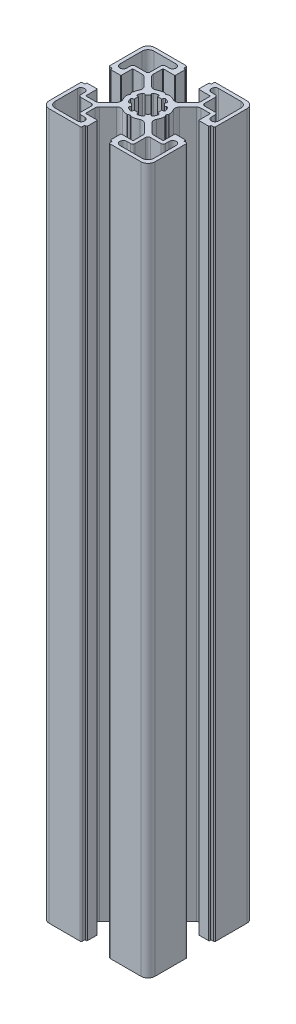
SolidWorks part; units mm, degrees
ref_plane "Front Plane" through (0, 0, 0) normal (0, 0, 1) x (1, 0, 0)
ref_plane "Top Plane" through (0, 0, 0) normal (0, 1, 0) x (1, 0, 0)
ref_plane "Right Plane" through (0, 0, 0) normal (1, 0, 0) x (0, 0, -1)
sketch "Sketch1" plane through (0, 0, 0) normal (0, 1, 0) x (1, 0, 0)
  line L106 (-18, 9.0002) -> (-18, 10.55)
  line L107 (-21, 18.5) -> (-21, 9.0002)
  line L108 (-9, 21) -> (-18.5, 21)
  line L109 (-10.55, 18) -> (-9, 18)
  line L110 (0.9675, 5.4811) -> (0.8674, 4.9242)
  line L111 (2.864, 4.0985) -> (3.1913, 4.5626)
  line L112 (4.5668, 3.2081) -> (4.0897, 2.8765)
  line L113 (4.9205, 0.8878) -> (5.4897, 0.9862)
  line L114 (5.4898, -0.9862) -> (4.9205, -0.8878)
  line L115 (4.0897, -2.8765) -> (4.5668, -3.2082)
  line L116 (3.1914, -4.5627) -> (2.864, -4.0985)
  line L117 (0.8674, -4.9242) -> (0.9675, -5.4811)
  line L118 (-0.9675, -5.4811) -> (-0.8674, -4.9242)
  line L119 (-2.864, -4.0985) -> (-3.1913, -4.5626)
  line L120 (-4.5668, -3.2082) -> (-4.0897, -2.8765)
  line L121 (-4.9205, -0.8878) -> (-5.4897, -0.9862)
  line L122 (-5.4899, 0.9862) -> (-4.9205, 0.8878)
  line L123 (-4.0897, 2.8765) -> (-4.5668, 3.2081)
  line L124 (-3.1914, 4.5627) -> (-2.864, 4.0985)
  line L125 (-0.8674, 4.9242) -> (-0.9675, 5.4811)
  line L126 (-11.55, 12.55) -> (-11.55, 17)
  line L127 (-17, 11.55) -> (-12.55, 11.55)
  line L128 (-21, -9.0002) -> (-21, -18.5)
  line L129 (-18, -10.55) -> (-18, -9.0002)
  line L130 (-12.55, -11.55) -> (-17, -11.55)
  line L131 (-11.55, -17) -> (-11.55, -12.55)
  line L132 (-9, -18) -> (-10.55, -18)
  line L133 (-18.5, -21) -> (-9, -21)
  line L134 (21, 9.0002) -> (21, 18.5)
  line L135 (18, 10.55) -> (18, 9.0002)
  line L136 (12.55, 11.55) -> (17, 11.55)
  line L137 (11.55, 17) -> (11.55, 12.55)
  line L138 (9, 18) -> (10.55, 18)
  line L139 (18.5, 21) -> (9, 21)
  line L140 (17, -11.55) -> (12.55, -11.55)
  line L141 (18, -9.0002) -> (18, -10.55)
  line L142 (21, -18.5) -> (21, -9.0002)
  line L143 (9, -21) -> (18.5, -21)
  line L144 (10.55, -18) -> (9, -18)
  line L145 (11.55, -12.55) -> (11.55, -17)
  line L146 (7.5635, 5.8587) -> (11.1298, 9.425)
  line L147 (12.5048, 9.9945) -> (16.3169, 9.9945)
  line L148 (16.5169, 9.7945) -> (16.5169, 5.2)
  line L149 (16.7169, 5) -> (20.7196, 5)
  line L150 (21.0196, 5.3) -> (21.0196, 5.5)
  line L151 (21.3196, 5.8) -> (22, 5.8)
  line L152 (22.5, 6.3) -> (22.5, 19.5)
  line L153 (19.5, 22.5) -> (6.3757, 22.5)
  line L154 (5.8757, 22) -> (5.8757, 21.3)
  line L155 (5.5757, 21) -> (5.3, 21)
  line L156 (5, 20.7) -> (5, 16.6668)
  line L157 (5.2, 16.4668) -> (9.9054, 16.4668)
  line L158 (10.1054, 16.2668) -> (10.1054, 12.4716)
  line L159 (9.5196, 11.0574) -> (5.9449, 7.4827)
  line L160 (0.7548, 7.9748) -> (0.1126, 7.6069)
  line L161 (-0.1126, 7.6069) -> (-0.7547, 7.9748)
  line L162 (-5.9449, 7.4827) -> (-9.5196, 11.0574)
  line L163 (-10.1054, 12.4716) -> (-10.1054, 16.2668)
  line L164 (-9.9054, 16.4668) -> (-5.2, 16.4668)
  line L165 (-5, 16.6668) -> (-5, 20.7)
  line L166 (-5.3, 21) -> (-5.5757, 21)
  line L167 (-5.8757, 21.3) -> (-5.8757, 22)
  line L168 (-6.3757, 22.5) -> (-19.5, 22.5)
  line L169 (-22.5, 19.5) -> (-22.5, 6.3)
  line L170 (-22, 5.8) -> (-21.3196, 5.8)
  line L171 (-21.0196, 5.5) -> (-21.0196, 5.3)
  line L172 (-20.7196, 5) -> (-16.7169, 5)
  line L173 (-16.5169, 5.2) -> (-16.5169, 9.7945)
  line L174 (-16.3169, 9.9945) -> (-12.5048, 9.9945)
  line L175 (-11.1298, 9.425) -> (-7.5635, 5.8587)
  line L176 (-7.974, 0.7926) -> (-7.5401, 0.0468)
  line L177 (-7.5401, -0.0468) -> (-7.974, -0.7926)
  line L178 (-7.5635, -5.8587) -> (-11.1298, -9.425)
  line L179 (-12.5048, -9.9945) -> (-16.3169, -9.9945)
  line L180 (-16.5169, -9.7945) -> (-16.5169, -5.2)
  line L181 (-16.7169, -5) -> (-20.7196, -5)
  line L182 (-21.0196, -5.3) -> (-21.0196, -5.5)
  line L183 (-21.3196, -5.8) -> (-22, -5.8)
  line L184 (-22.5, -6.3) -> (-22.5, -19.5)
  line L185 (-19.5, -22.5) -> (-6.3757, -22.5)
  line L186 (-5.8757, -22) -> (-5.8757, -21.3)
  line L187 (-5.5757, -21) -> (-5.3, -21)
  line L188 (-5, -20.7) -> (-5, -16.6668)
  line L189 (-5.2, -16.4668) -> (-9.9054, -16.4668)
  line L190 (-10.1054, -16.2668) -> (-10.1054, -12.4716)
  line L191 (-9.5196, -11.0574) -> (-5.9449, -7.4827)
  line L192 (-0.7547, -7.9748) -> (-0.1126, -7.6069)
  line L193 (0.1126, -7.6069) -> (0.7548, -7.9748)
  line L194 (5.9449, -7.4827) -> (9.5196, -11.0574)
  line L195 (10.1054, -12.4716) -> (10.1054, -16.2668)
  line L196 (9.9054, -16.4668) -> (5.2, -16.4668)
  line L197 (5, -16.6668) -> (5, -20.7)
  line L198 (5.3, -21) -> (5.5757, -21)
  line L199 (5.8757, -21.3) -> (5.8757, -22)
  line L200 (6.3757, -22.5) -> (19.5, -22.5)
  line L201 (22.5, -19.5) -> (22.5, -6.3)
  line L202 (22, -5.8) -> (21.3196, -5.8)
  line L203 (21.0196, -5.5) -> (21.0196, -5.3)
  line L204 (20.7196, -5) -> (16.7169, -5)
  line L205 (16.5169, -5.2) -> (16.5169, -9.7945)
  line L206 (16.3169, -9.9945) -> (12.5048, -9.9945)
  line L207 (11.1298, -9.425) -> (7.5635, -5.8587)
  line L208 (7.974, -0.7926) -> (7.5401, -0.0468)
  line L209 (7.5401, 0.0468) -> (7.974, 0.7926)
  arc A140 (-17, 11.55) -> (-18, 10.55) centre (-17, 10.55) ccw
  arc A141 (-21, 9.0002) -> (-18, 9.0002) centre (-19.5, 9.0002) ccw
  arc A142 (-18.5, 21) -> (-21, 18.5) centre (-18.5, 18.5) ccw
  arc A143 (-9, 18) -> (-9, 21) centre (-9, 19.5) ccw
  arc A144 (-10.55, 18) -> (-11.55, 17) centre (-10.55, 17) ccw
  arc A145 (-12.55, 11.55) -> (-11.55, 12.55) centre (-12.55, 12.55) ccw
  arc A146 (-21, -18.5) -> (-18.5, -21) centre (-18.5, -18.5) ccw
  arc A147 (-18, -9.0002) -> (-21, -9.0002) centre (-19.5, -9.0002) ccw
  arc A148 (-18, -10.55) -> (-17, -11.55) centre (-17, -10.55) ccw
  arc A149 (-11.55, -12.55) -> (-12.55, -11.55) centre (-12.55, -12.55) ccw
  arc A150 (-11.55, -17) -> (-10.55, -18) centre (-10.55, -17) ccw
  arc A151 (-9, -21) -> (-9, -18) centre (-9, -19.5) ccw
  arc A152 (0.8674, 4.9242) -> (-0.8674, 4.9242) centre (0, 0) ccw
  arc A153 (1.5951, 5.8941) -> (0.9675, 5.4811) centre (1.4627, 5.4119) ccw
  arc A154 (3.0417, 5.301) -> (1.5951, 5.8941) centre (0.0235, 0) ccw
  arc A155 (3.1913, 4.5626) -> (3.0417, 5.301) centre (2.7943, 4.8665) ccw
  arc A156 (4.0897, 2.8765) -> (2.864, 4.0985) centre (0, 0) ccw
  arc A157 (5.3025, 3.0565) -> (4.5668, 3.2081) centre (4.868, 2.8091) ccw
  arc A158 (5.906, 1.6142) -> (5.3025, 3.0565) centre (0.0235, 0) ccw
  arc A159 (5.4897, 0.9862) -> (5.906, 1.6142) centre (5.4239, 1.4819) ccw
  arc A160 (4.9205, -0.8878) -> (4.9205, 0.8878) centre (0, 0) ccw
  arc A161 (5.906, -1.6142) -> (5.4898, -0.9862) centre (5.4239, -1.4819) ccw
  arc A162 (5.3025, -3.0564) -> (5.906, -1.6142) centre (0.0235, 0) ccw
  arc A163 (4.5668, -3.2082) -> (5.3025, -3.0564) centre (4.868, -2.8091) ccw
  arc A164 (2.864, -4.0985) -> (4.0897, -2.8765) centre (0, 0) ccw
  arc A165 (3.0416, -5.301) -> (3.1914, -4.5627) centre (2.7943, -4.8665) ccw
  arc A166 (1.5951, -5.8941) -> (3.0416, -5.301) centre (0.0235, 0) ccw
  arc A167 (0.9675, -5.4811) -> (1.5951, -5.8941) centre (1.4627, -5.4119) ccw
  arc A168 (-0.8674, -4.9242) -> (0.8674, -4.9242) centre (0, 0) ccw
  arc A169 (-1.5951, -5.8941) -> (-0.9675, -5.4811) centre (-1.4627, -5.4119) ccw
  arc A170 (-3.0416, -5.301) -> (-1.5951, -5.8941) centre (-0.0235, 0) ccw
  arc A171 (-3.1913, -4.5626) -> (-3.0416, -5.301) centre (-2.7943, -4.8665) ccw
  arc A172 (-4.0897, -2.8765) -> (-2.864, -4.0985) centre (0, 0) ccw
  arc A173 (-5.3025, -3.0565) -> (-4.5668, -3.2082) centre (-4.868, -2.8091) ccw
  arc A174 (-5.906, -1.6142) -> (-5.3025, -3.0565) centre (-0.0235, 0) ccw
  arc A175 (-5.4897, -0.9862) -> (-5.906, -1.6142) centre (-5.4239, -1.4819) ccw
  arc A176 (-4.9205, 0.8878) -> (-4.9205, -0.8878) centre (0, 0) ccw
  arc A177 (-5.906, 1.6141) -> (-5.4899, 0.9862) centre (-5.4239, 1.4818) ccw
  arc A178 (-5.3025, 3.0564) -> (-5.906, 1.6141) centre (-0.0235, 0) ccw
  arc A179 (-4.5668, 3.2081) -> (-5.3025, 3.0564) centre (-4.868, 2.8091) ccw
  arc A180 (-2.864, 4.0985) -> (-4.0897, 2.8765) centre (0, 0) ccw
  arc A181 (-3.0417, 5.301) -> (-3.1914, 4.5627) centre (-2.7943, 4.8665) ccw
  arc A182 (-1.5951, 5.8941) -> (-3.0417, 5.301) centre (-0.0235, 0) ccw
  arc A183 (-0.9675, 5.4811) -> (-1.5951, 5.8941) centre (-1.4627, 5.4119) ccw
  arc A184 (21, 18.5) -> (18.5, 21) centre (18.5, 18.5) ccw
  arc A185 (18, 9.0002) -> (21, 9.0002) centre (19.5, 9.0002) ccw
  arc A186 (18, 10.55) -> (17, 11.55) centre (17, 10.55) ccw
  arc A187 (11.55, 12.55) -> (12.55, 11.55) centre (12.55, 12.55) ccw
  arc A188 (11.55, 17) -> (10.55, 18) centre (10.55, 17) ccw
  arc A189 (9, 21) -> (9, 18) centre (9, 19.5) ccw
  arc A190 (12.55, -11.55) -> (11.55, -12.55) centre (12.55, -12.55) ccw
  arc A191 (17, -11.55) -> (18, -10.55) centre (17, -10.55) ccw
  arc A192 (21, -9.0002) -> (18, -9.0002) centre (19.5, -9.0002) ccw
  arc A193 (18.5, -21) -> (21, -18.5) centre (18.5, -18.5) ccw
  arc A194 (9, -18) -> (9, -21) centre (9, -19.5) ccw
  arc A195 (10.55, -18) -> (11.55, -17) centre (10.55, -17) ccw
  arc A196 (7.9999, 0.9154) -> (7.2004, 3.6119) centre (0.0496, 0.0249) ccw
  arc A197 (7.5635, 5.8587) -> (7.2004, 3.6119) centre (8.9385, 4.4837) ccw
  arc A198 (12.5048, 9.9945) -> (11.1298, 9.425) centre (12.5048, 8.05) ccw
  arc A199 (16.5169, 9.7945) -> (16.3169, 9.9945) centre (16.3169, 9.7945) ccw
  arc A200 (16.5169, 5.2) -> (16.7169, 5) centre (16.7169, 5.2) ccw
  arc A201 (20.7196, 5) -> (21.0196, 5.3) centre (20.7196, 5.3) ccw
  arc A202 (21.3196, 5.8) -> (21.0196, 5.5) centre (21.3196, 5.5) ccw
  arc A203 (22, 5.8) -> (22.5, 6.3) centre (22, 6.3) ccw
  arc A204 (22.5, 19.5) -> (19.5, 22.5) centre (19.5, 19.5) ccw
  arc A205 (6.3757, 22.5) -> (5.8757, 22) centre (6.3757, 22) ccw
  arc A206 (5.5757, 21) -> (5.8757, 21.3) centre (5.5757, 21.3) ccw
  arc A207 (5.3, 21) -> (5, 20.7) centre (5.3, 20.7) ccw
  arc A208 (5, 16.6668) -> (5.2, 16.4668) centre (5.2, 16.6668) ccw
  arc A209 (10.1054, 16.2668) -> (9.9054, 16.4668) centre (9.9054, 16.2668) ccw
  arc A210 (9.5196, 11.0574) -> (10.1054, 12.4716) centre (8.1054, 12.4716) ccw
  arc A211 (3.6665, 7.1733) -> (5.9449, 7.4827) centre (4.5855, 8.9496) ccw
  arc A212 (3.6665, 7.1733) -> (0.8753, 8.0001) centre (0.0235, 0) ccw
  arc A213 (0.8753, 8.0001) -> (0.7548, 7.9748) centre (0.8542, 7.8013) ccw
  arc A214 (0, 7.531) -> (0.1126, 7.6069) centre (-0.0489, 7.7249) ccw
  arc A215 (-0.1126, 7.6069) -> (0, 7.531) centre (0.0489, 7.7249) ccw
  arc A216 (-0.7547, 7.9748) -> (-0.8753, 8.0001) centre (-0.8542, 7.8013) ccw
  arc A217 (-0.8753, 8.0001) -> (-3.6665, 7.1733) centre (-0.0235, 0) ccw
  arc A218 (-5.9449, 7.4827) -> (-3.6665, 7.1733) centre (-4.5855, 8.9496) ccw
  arc A219 (-10.1054, 12.4716) -> (-9.5196, 11.0574) centre (-8.1054, 12.4716) ccw
  arc A220 (-9.9054, 16.4668) -> (-10.1054, 16.2668) centre (-9.9054, 16.2668) ccw
  arc A221 (-5.2, 16.4668) -> (-5, 16.6668) centre (-5.2, 16.6668) ccw
  arc A222 (-5, 20.7) -> (-5.3, 21) centre (-5.3, 20.7) ccw
  arc A223 (-5.8757, 21.3) -> (-5.5757, 21) centre (-5.5757, 21.3) ccw
  arc A224 (-5.8757, 22) -> (-6.3757, 22.5) centre (-6.3757, 22) ccw
  arc A225 (-19.5, 22.5) -> (-22.5, 19.5) centre (-19.5, 19.5) ccw
  arc A226 (-22.5, 6.3) -> (-22, 5.8) centre (-22, 6.3) ccw
  arc A227 (-21.0196, 5.5) -> (-21.3196, 5.8) centre (-21.3196, 5.5) ccw
  arc A228 (-21.0196, 5.3) -> (-20.7196, 5) centre (-20.7196, 5.3) ccw
  arc A229 (-16.7169, 5) -> (-16.5169, 5.2) centre (-16.7169, 5.2) ccw
  arc A230 (-16.3169, 9.9945) -> (-16.5169, 9.7945) centre (-16.3169, 9.7945) ccw
  arc A231 (-11.1298, 9.425) -> (-12.5048, 9.9945) centre (-12.5048, 8.05) ccw
  arc A232 (-7.2004, 3.6119) -> (-7.5635, 5.8587) centre (-8.9385, 4.4837) ccw
  arc A233 (-7.2004, 3.6119) -> (-7.9999, 0.9154) centre (-0.0496, 0.0249) ccw
  arc A234 (-7.9999, 0.9154) -> (-7.974, 0.7926) centre (-7.8011, 0.8932) ccw
  arc A235 (-7.5313, 0) -> (-7.5401, 0.0468) centre (-7.7309, -0.013) ccw
  arc A236 (-7.5401, -0.0468) -> (-7.5313, 0) centre (-7.7309, 0.013) ccw
  arc A237 (-7.974, -0.7926) -> (-7.9999, -0.9154) centre (-7.8011, -0.8932) ccw
  arc A238 (-7.9999, -0.9154) -> (-7.2004, -3.6119) centre (-0.0496, -0.0249) ccw
  arc A239 (-7.5635, -5.8587) -> (-7.2004, -3.6119) centre (-8.9385, -4.4837) ccw
  arc A240 (-12.5048, -9.9945) -> (-11.1298, -9.425) centre (-12.5048, -8.05) ccw
  arc A241 (-16.5169, -9.7945) -> (-16.3169, -9.9945) centre (-16.3169, -9.7945) ccw
  arc A242 (-16.5169, -5.2) -> (-16.7169, -5) centre (-16.7169, -5.2) ccw
  arc A243 (-20.7196, -5) -> (-21.0196, -5.3) centre (-20.7196, -5.3) ccw
  arc A244 (-21.3196, -5.8) -> (-21.0196, -5.5) centre (-21.3196, -5.5) ccw
  arc A245 (-22, -5.8) -> (-22.5, -6.3) centre (-22, -6.3) ccw
  arc A246 (-22.5, -19.5) -> (-19.5, -22.5) centre (-19.5, -19.5) ccw
  arc A247 (-6.3757, -22.5) -> (-5.8757, -22) centre (-6.3757, -22) ccw
  arc A248 (-5.5757, -21) -> (-5.8757, -21.3) centre (-5.5757, -21.3) ccw
  arc A249 (-5.3, -21) -> (-5, -20.7) centre (-5.3, -20.7) ccw
  arc A250 (-5, -16.6668) -> (-5.2, -16.4668) centre (-5.2, -16.6668) ccw
  arc A251 (-10.1054, -16.2668) -> (-9.9054, -16.4668) centre (-9.9054, -16.2668) ccw
  arc A252 (-9.5196, -11.0574) -> (-10.1054, -12.4716) centre (-8.1054, -12.4716) ccw
  arc A253 (-3.6665, -7.1733) -> (-5.9449, -7.4827) centre (-4.5855, -8.9496) ccw
  arc A254 (-3.6665, -7.1733) -> (-0.8753, -8.0001) centre (-0.0235, 0) ccw
  arc A255 (-0.8753, -8.0001) -> (-0.7547, -7.9748) centre (-0.8542, -7.8013) ccw
  arc A256 (0, -7.531) -> (-0.1126, -7.6069) centre (0.0489, -7.7249) ccw
  arc A257 (0.1126, -7.6069) -> (0, -7.531) centre (-0.0489, -7.7249) ccw
  arc A258 (0.7548, -7.9748) -> (0.8753, -8.0001) centre (0.8542, -7.8012) ccw
  arc A259 (0.8753, -8.0001) -> (3.6665, -7.1733) centre (0.0235, 0) ccw
  arc A260 (5.9449, -7.4827) -> (3.6665, -7.1733) centre (4.5855, -8.9496) ccw
  arc A261 (10.1054, -12.4716) -> (9.5196, -11.0574) centre (8.1054, -12.4716) ccw
  arc A262 (9.9054, -16.4668) -> (10.1054, -16.2668) centre (9.9054, -16.2668) ccw
  arc A263 (5.2, -16.4668) -> (5, -16.6668) centre (5.2, -16.6668) ccw
  arc A264 (5, -20.7) -> (5.3, -21) centre (5.3, -20.7) ccw
  arc A265 (5.8757, -21.3) -> (5.5757, -21) centre (5.5757, -21.3) ccw
  arc A266 (5.8757, -22) -> (6.3757, -22.5) centre (6.3757, -22) ccw
  arc A267 (19.5, -22.5) -> (22.5, -19.5) centre (19.5, -19.5) ccw
  arc A268 (22.5, -6.3) -> (22, -5.8) centre (22, -6.3) ccw
  arc A269 (21.0196, -5.5) -> (21.3196, -5.8) centre (21.3196, -5.5) ccw
  arc A270 (21.0196, -5.3) -> (20.7196, -5) centre (20.7196, -5.3) ccw
  arc A271 (16.7169, -5) -> (16.5169, -5.2) centre (16.7169, -5.2) ccw
  arc A272 (16.3169, -9.9945) -> (16.5169, -9.7945) centre (16.3169, -9.7945) ccw
  arc A273 (11.1298, -9.425) -> (12.5048, -9.9945) centre (12.5048, -8.05) ccw
  arc A274 (7.2004, -3.6119) -> (7.5635, -5.8587) centre (8.9385, -4.4837) ccw
  arc A275 (7.2004, -3.6119) -> (7.9999, -0.9154) centre (0.0496, -0.0249) ccw
  arc A276 (7.9999, -0.9154) -> (7.974, -0.7926) centre (7.8011, -0.8932) ccw
  arc A277 (7.5313, 0) -> (7.5401, -0.0468) centre (7.7309, 0.013) ccw
  arc A278 (7.5401, 0.0468) -> (7.5313, 0) centre (7.7309, -0.013) ccw
  arc A279 (7.974, 0.7926) -> (7.9999, 0.9154) centre (7.8011, 0.8932) ccw
extrude "Boss-Extrude1" add sketch "Sketch1" along normal blind 300
